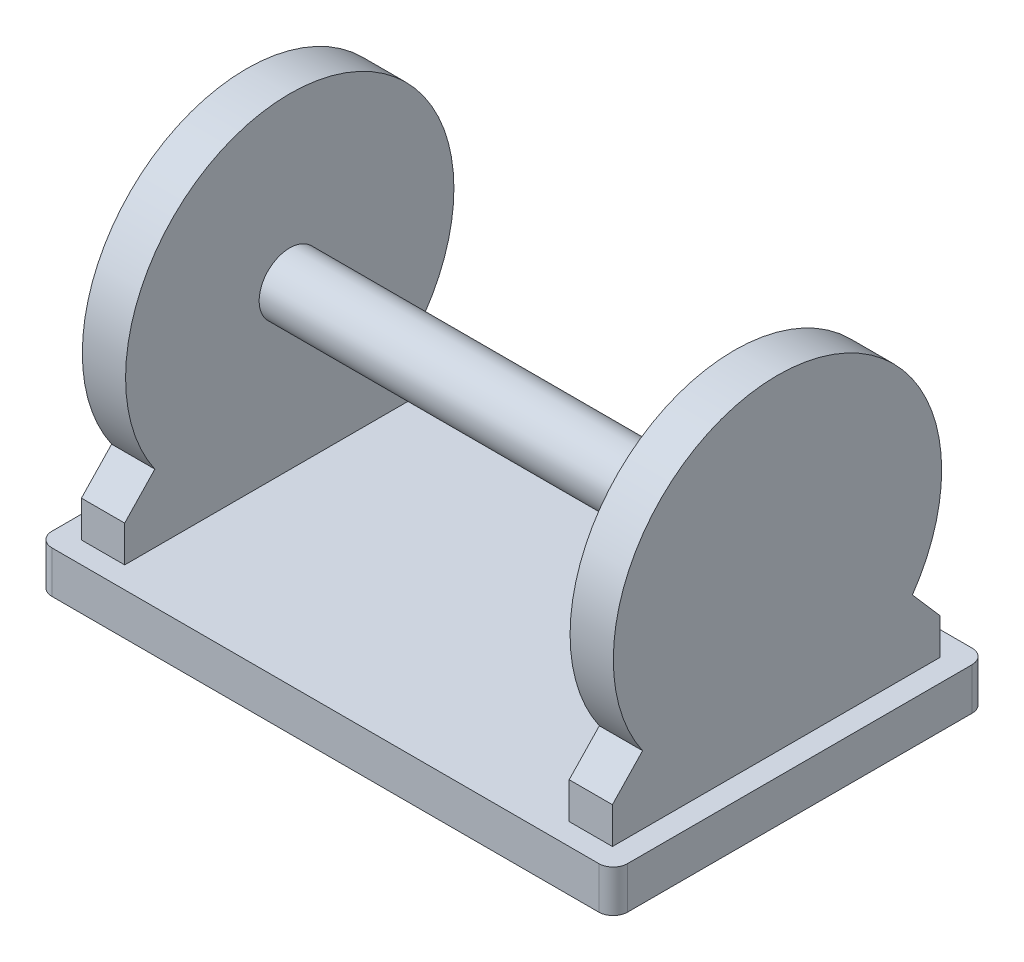
SolidWorks part; units mm, degrees
ref_plane "Front Plane" through (0, 0, 0) normal (0, 0, 1) x (1, 0, 0)
ref_plane "Top Plane" through (0, 0, 0) normal (0, 1, 0) x (1, 0, 0)
ref_plane "Right Plane" through (0, 0, 0) normal (1, 0, 0) x (0, 0, -1)
sketch "Sketch2" plane through (0, 0, 0) normal (0, 1, 0) x (1, 0, 0)
  line L0 (-39.94, 25.9) -> (39.94, -25.9) construction
  line L1 (-39.94, 25.9) -> (39.94, 25.9)
  line L2 (-39.94, 25.9) -> (-39.94, -25.9)
  line L3 (-39.94, -25.9) -> (39.94, -25.9)
  line L4 (39.94, 25.9) -> (39.94, -25.9)
  line L5 (39.94, -25.9) -> (34.725, -27.2276) construction
  dimension "D1" = 79.88
  dimension "D2" = 51.8
extrude "Boss-Extrude1" add sketch "Sketch2" along normal blind 5.84
fillet "Fillet2" radius 2 1 edges at (-39.94, 2.92, -25.9)
fillet "Fillet3" radius 2 1 edges at (-39.94, 2.92, 25.9)
fillet "Fillet4" radius 2 1 edges at (39.94, 2.92, -25.9)
sketch "Sketch3" plane through (-39.94, 0, 0) normal (-1, 0, 0) x (0, 0, 1)
  line L0 (0, 5.84) -> (0, 0) construction
  line L1 (-23.9, 5.84) -> (23.9, 5.84) construction
  line L2 (-23.9, 2.92) -> (23.9, 2.92) construction
  line L3 (-23.9, 5.84) -> (-23.9, 0) construction
  line L4 (23.9, 0) -> (23.9, 5.84) construction
  line L5 (0, 5.84) -> (0, 50.94) construction
  line L6 (-22.5436, 5.84) -> (22.9064, 5.84)
  line L7 (-22.5436, 5.84) -> (-22.5436, 10.87)
  line L9 (22.9064, 5.84) -> (22.9064, 10.87)
  line L10 (0, 50.94) -> (0, 28.39) construction
  line L11 (-18.7203, 15.26) -> (-22.5436, 10.87)
  line L12 (18.7203, 15.26) -> (22.9064, 10.87)
  arc A0 (18.7203, 15.26) -> (-18.7203, 15.26) centre (0, 28.24) ccw
  dimension "D4" = 22.7
  dimension "D3" = 45.1
  dimension "D5" = 5.03
  dimension "D6" = 5.03
extrude "Boss-Extrude3" add sketch "Sketch3" against normal blind 6 from offset 3.1 offset against normal yes
fillet "Fillet6" radius 2 1 edges at (39.94, 2.92, 25.9)
mirror "Mirror1" about plane through (0, 0, 0) normal (1, 0, 0) of "Boss-Extrude3"
sketch "Sketch10" plane through (-30.84, 0, 0) normal (1, 0, 0) x (0, 0, -1)
  line L0 (-22.78, 28.24) -> (22.78, 28.24) construction
  circle A0 centre (0, 28.24) radius 4.2495
  arc A1 (18.7203, 15.26) -> (-18.7203, 15.26) centre (0, 28.24) ccw construction
extrude "Boss-Extrude5" add sketch "Sketch10" along normal up to next
